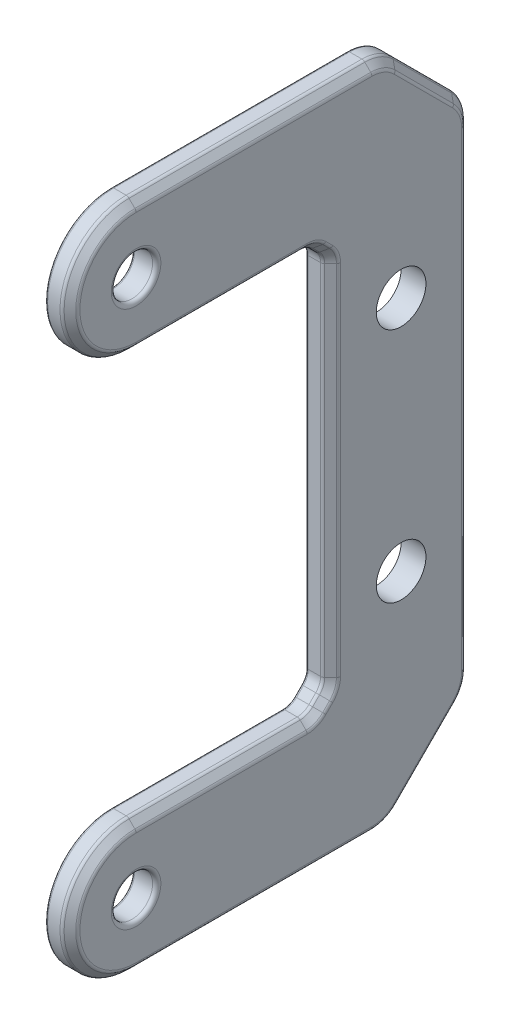
SolidWorks part; units mm, degrees
material "moto_black"
ref_plane "Front Plane" through (0, 0, 0) normal (0, 0, 1) x (1, 0, 0)
ref_plane "Top Plane" through (0, 0, 0) normal (0, 1, 0) x (1, 0, 0)
ref_plane "Right Plane" through (0, 0, 0) normal (1, 0, 0) x (0, 0, -1)
sketch "Sketch1" plane through (0, 0, 0) normal (1, 0, 0) x (0, 0, -1)
  line L0 (30.59, 8) -> (40.59, -2)
  line L5 (0, 8) -> (30.59, 8)
  line L6 (40.59, -2) -> (40.59, -63)
  line L11 (0, -8) -> (21.5227, -8)
  line L12 (23.5227, -10) -> (23.5227, -55)
  line L13 (21.5227, -8) -> (23.5227, -10)
  line L14 (0, -73) -> (30.59, -73)
  line L19 (30.59, -73) -> (40.59, -63)
  line L20 (5.5188, -32.5) -> (10.8394, -32.5)
  line L21 (21.5227, -57) -> (23.5227, -55)
  line L22 (0, -57) -> (21.5227, -57)
  circle A0 centre (0, 0) radius 5
  circle A3 centre (0, 0) radius 8
  circle A4 centre (0, -65) radius 5
  circle A5 centre (0, -65) radius 8
  circle A6 centre (0, 0) radius 2.5
  circle A7 centre (0, -65) radius 2.5
  point P0 (0, 0)
  point P3 (40.59, 8)
  point P11 (23.5227, -8)
  point P22 (40.59, -32.5)
  point P27 (23.5227, -32.5)
  dimension "D3" = 10
  dimension "D2" = 5
  dimension "D1" = 3
extrude "Boss-Extrude1" add sketch "Sketch1" along normal blind 3 contours L22 A5 L14 L19 L6 L0 L5 A3 L11 L13 L12 L21 | A3 A0 | A5 A4 | A6 | A7
fillet "Fillet4" radius 5 4 edges at (1.5, -73, -30.59) (1.5, -63, -40.59) (1.5, 8, -30.59) (1.5, -2, -40.59)
fillet "Fillet5" radius 2 4 edges at (1.5, -10, -23.5227) (1.5, -8, -21.5227) (1.5, -57, -21.5227) (1.5, -55, -23.5227)
fillet "Fillet6" radius 0.3 22 edges at (0, -62.8423, -40.2094) (0, -32.5, -40.59) (0, -2.1577, -40.2094) (0, 3, -35.59) (0, 7.6194, -30.4323) (0, 8, -14.2595) (0, 0, 8) (0, -8, -10.3471) (0, -8.1522, -21.4596) (0, -9, -22.5227) (0, -10.0631, -23.3705) (0, -32.5, -23.5227) (0, -54.9369, -23.3705) (0, -56, -22.5227) (0, -56.8478, -21.4596) (0, -57, -10.3471) (0, -65, 8) (0, -73, -14.2595) (0, -72.6194, -30.4323) (0, -68, -35.59) (0, 0, -2.5) (0, -65, 2.5)
chamfer "Chamfer4" distance 1 angle 45 20 edges at (3, -73, -14.2595) (3, -72.6194, -30.4323) (3, -65, 8) (3, -68, -35.59) (3, -57, -10.3471) (3, -62.8423, -40.2094) (3, -56.8478, -21.4596) (3, -32.5, -40.59) (3, -56, -22.5227) (3, -2.1577, -40.2094) (3, -54.9369, -23.3705) (3, 3, -35.59) (3, -32.5, -23.5227) (3, 7.6194, -30.4323) (3, -10.0631, -23.3705) (3, 8, -14.2595) (3, -9, -22.5227) (3, 0, 8) (3, -8.1522, -21.4596) (3, -8, -10.3471)
fillet "Fillet7" radius 0.5 40 edges at (2, 7.6194, -30.4323) (2, 8, -14.2595) (2, 0, 8) (2, -8, -10.3471) (2, -8.1522, -21.4596) (2, -9, -22.5227) (2, -10.0631, -23.3705) (2, -32.5, -23.5227) (2, -54.9369, -23.3705) (2, -56, -22.5227) (2, -56.8478, -21.4596) (2, -57, -10.3471) (2, -65, 8) (2, -73, -14.2595) (2, -72.6194, -30.4323) (2, -68, -35.59) (2, -62.8423, -40.2094) (2, -32.5, -40.59) (2, -2.1577, -40.2094) (3, -2.5403, -39.2855) (3, -32.5, -39.59) (3, -62.4597, -39.2855) (3, -67.2929, -34.8829) (3, -71.6955, -30.0497) (3, -72, -14.2595) (3, -65, 7) (3, -58, -10.3471) (3, -57.7716, -21.8423) (3, -56.7071, -23.2298) (3, -55.3196, -24.2943) (3, -32.5, -24.5227) (3, -9.6804, -24.2943) (3, -8.2929, -23.2298) (3, -7.2284, -21.8423) (3, -7, -10.3471) (3, 0, 7) (3, 7, -14.2595) (3, 6.6955, -30.0497) (2, 3, -35.59) (3, 2.2929, -34.8829)
fillet "Fillet9" radius 0.5 2 edges at (3, -65, 2.5) (3, 0, -2.5)
sketch "Sketch2" plane through (3, 0, 0) normal (1, 0, 0) x (0, 0, -1)
  line L0 (24.7298, -32.5) -> (39.3829, -32.5)
  line L1 (24.7298, -10.8284) -> (24.7298, -54.1716) construction
  line L2 (39.3829, -60.9289) -> (39.3829, -4.0711) construction
  circle A0 centre (32.0564, -18.1891) radius 3
  circle A1 centre (32.0564, -46.8109) radius 3
  dimension "D1" = 6
extrude "Cut-Extrude1" cut sketch "Sketch2" against normal blind 10 contours A0 | A1
